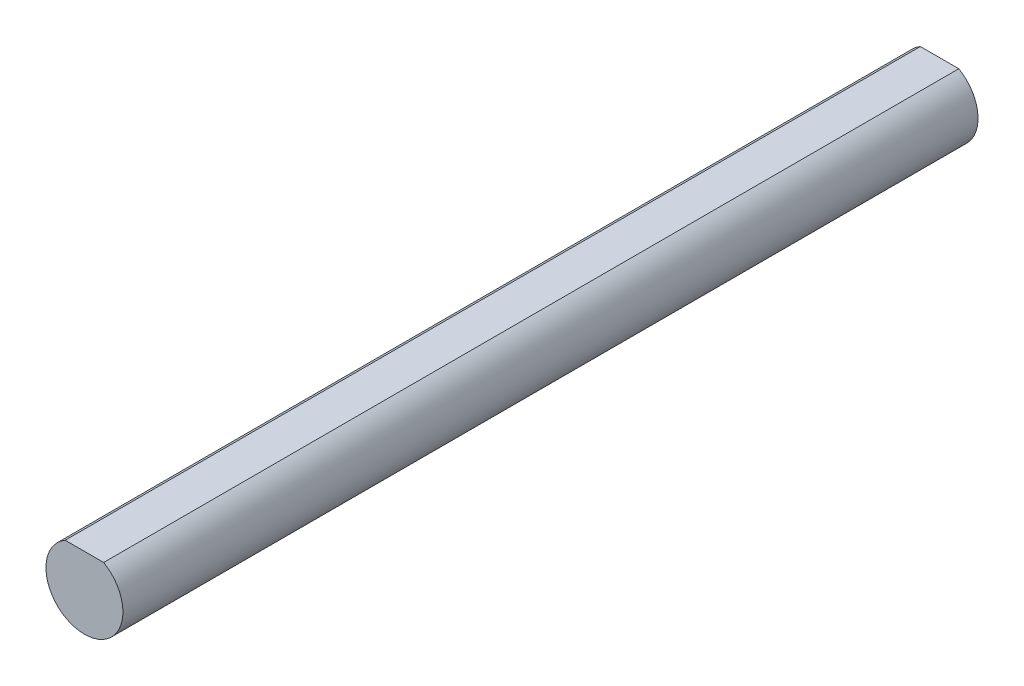
SolidWorks part; units mm, degrees
ref_plane "Front Plane" through (0, 0, 0) normal (0, 0, 1) x (1, 0, 0)
ref_plane "Top Plane" through (0, 0, 0) normal (0, 1, 0) x (1, 0, 0)
ref_plane "Right Plane" through (0, 0, 0) normal (1, 0, 0) x (0, 0, -1)
sketch "Sketch1" plane through (0, 0, 0) normal (0, 0, 1) x (1, 0, 0)
  line L0 (-1, 1.7321) -> (1, 1.7321) construction
  circle A1 centre (0, 0) radius 2 construction
  dimension "Diameter" = 4
  dimension "Flat Width" = 2
sketch "Sketch2" plane through (0, 0, 0) normal (1, 0, 0) x (0, 0, -1)
  line L0 (-76.2, 2) -> (76.2, 2) construction
  line L1 (0, 2) -> (0, -2) construction
  line L2 (0, 2) -> (0, -2) construction
  line L3 (-76.2, 2) -> (-76.2, -2) construction
  line L4 (-76.2, -2) -> (76.2, -2) construction
  point P2 (0, 2)
  point P3 (68.2, 2)
  point P4 (-68.2, 2)
  dimension "Length" = 152.4
  dimension "D2" = 8
  dimension "D1" = 8
  dimension "D-Profile Length" = 152.4
sketch "Sketch3" plane through (0, 0, 0) normal (0, 0, 1) x (1, 0, 0)
  circle A1 centre (0, 0) radius 2 construction
  circle A3 centre (0, 0) radius 2
extrude "Boss-Extrude2" add sketch "Sketch3" along normal up to vertex (76.2 mm away) up to point (0, 2, 76.2)
sketch "Sketch10" plane through (0, 0, 0) normal (0, 0, 1) x (1, 0, 0)
  line L0 (-1, 1.7321) -> (1, 1.7321)
  line L1 (0, 0) -> (0, 2) construction
  circle A0 centre (0, 0) radius 2 construction
  circle A1 centre (0, 0) radius 2 construction
  arc A2 (-1, 1.7321) -> (1, 1.7321) centre (0, 0) cw
extrude "Cut-Extrude5" cut sketch "Sketch10" against normal through all both and the other way through all
chamfer "Chamfer1" distance 0.2 angle 45 4 edges at (0, -2, 76.2) (0, -2, 0) (0, 1.7321, 0) (0, 1.7321, 76.2)
sketch "Sketch11" plane through (0, 0, 0) normal (0, 0, -1) x (-1, 0, 0)
  circle A0 centre (0, 0) radius 3.175
extrude "Cut-Extrude6" cut sketch "Sketch11" against normal blind 12.7
sketch "Sketch12" plane through (0, 0, 76.2) normal (0, 0, 1) x (1, 0, 0)
  circle A0 centre (0, 0) radius 2
extrude "Cut-Extrude7" cut sketch "Sketch12" against normal blind 19.05
equation "\"D1@Chamfer1\"= \"Diameter@Sketch1\" / 20"
equation "\"D1@Sketch2\"=\"Diameter@Sketch1\"*2"
equation "\"D2@Sketch2\"=\"D1@Sketch2\""
